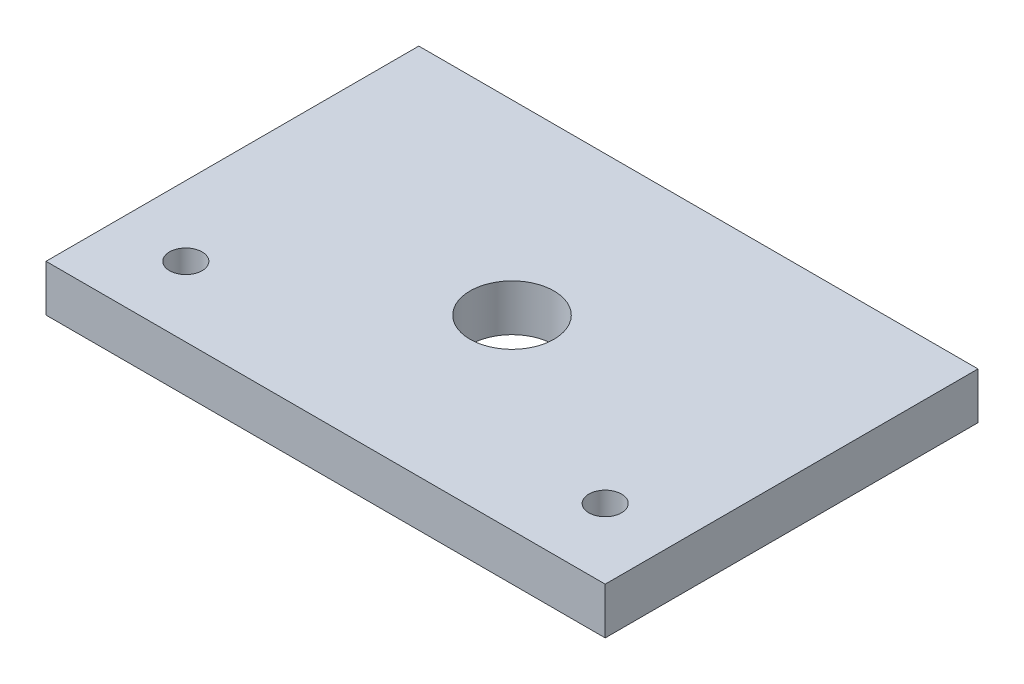
SolidWorks part; units mm, degrees
ref_plane "Front Plane" through (0, 0, 0) normal (0, 0, 1) x (1, 0, 0)
ref_plane "Top Plane" through (0, 0, 0) normal (0, 1, 0) x (1, 0, 0)
ref_plane "Right Plane" through (0, 0, 0) normal (1, 0, 0) x (0, 0, -1)
other "Configuration Table"
sketch "草图1" plane through (0, 0, 0) normal (0, 1, 0) x (1, 0, 0)
  line L1 (-60, -40) -> (60, -40)
  line L2 (-60, -40) -> (-60, 40)
  line L3 (-60, 40) -> (60, 40)
  line L4 (60, -40) -> (60, 40)
  line L5 (-60, -40) -> (60, 40) construction
  line L6 (-60, 40) -> (60, -40) construction
  circle A0 centre (0, 0) radius 9
  circle A1 centre (-45, -25) radius 3.5
  circle A2 centre (45, -25) radius 3.5
  point P0 (0, 0)
extrude "凸台-拉伸1" add sketch "草图1" along normal blind 10
